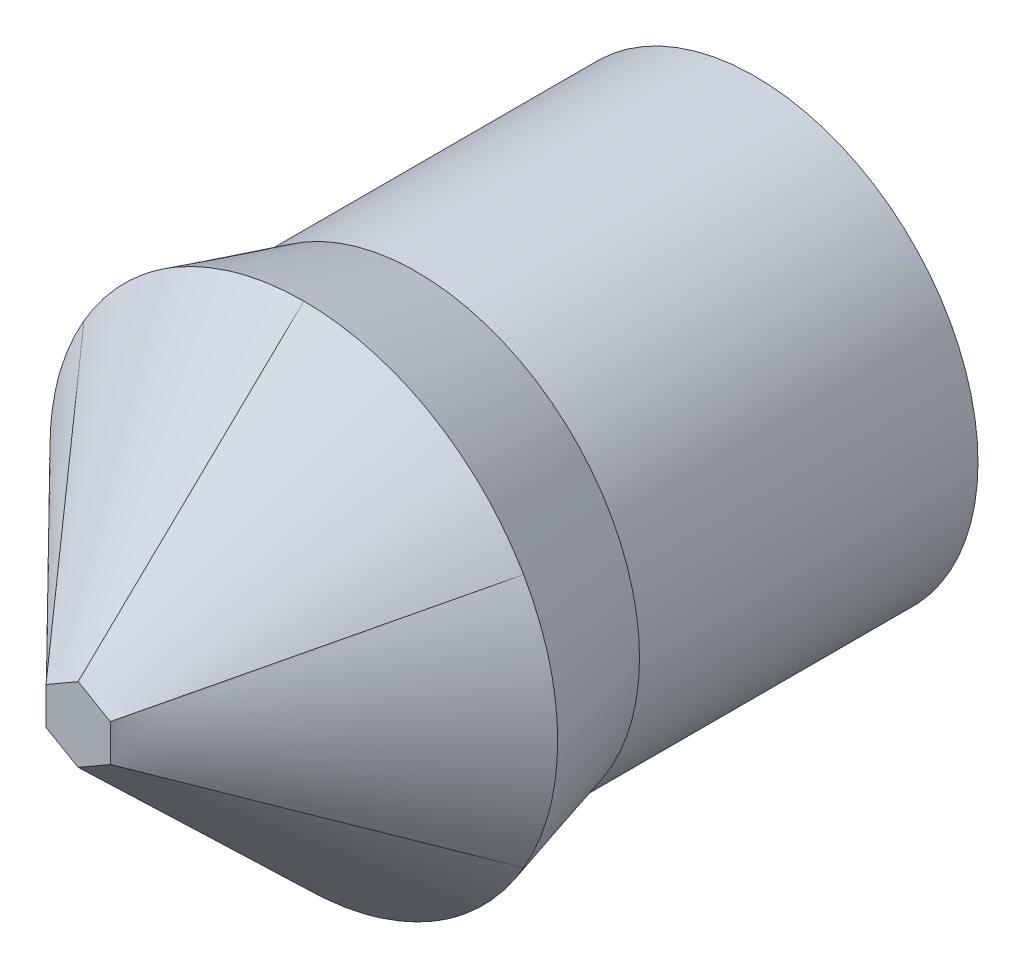
SolidWorks part; units mm, degrees
ref_plane "정면" through (0, 0, 0) normal (0, 0, 1) x (1, 0, 0)
ref_plane "윗면" through (0, 0, 0) normal (0, 1, 0) x (1, 0, 0)
ref_plane "우측면" through (0, 0, 0) normal (1, 0, 0) x (0, 0, -1)
sketch "스케치1" plane through (0, 0, 0) normal (0, 0, 1) x (1, 0, 0)
  circle A0 centre (0, 0) radius 3.95
  dimension "D1" = 7.9
extrude "보스-돌출1" add sketch "스케치1" along normal blind 6
sketch "스케치2" plane through (0, 0, 6) normal (0, 0, 1) x (1, 0, 0)
  circle A0 centre (0, 0) radius 3.95
ref_plane "평면1" through (0, 0, 8) normal (0, 0, 1) x (1, 0, 0)
sketch "스케치3" plane through (0, 0, 8) normal (0, 0, 1) x (1, 0, 0)
  circle A0 centre (0, 0) radius 4.5
  dimension "D1" = 9
loft "로프트1" add profiles "스케치3", "스케치2"
sketch "스케치4" plane through (0, 0, 8) normal (0, 0, 1) x (1, 0, 0)
  circle A0 centre (0, 0) radius 4.5
ref_plane "평면2" through (0, 0, 12) normal (0, 0, 1) x (1, 0, 0)
sketch "스케치5" plane through (0, 0, 12) normal (0, 0, 1) x (1, 0, 0)
  line L1 (0, -0.658) -> (0.5699, -0.329)
  line L2 (0.5699, -0.329) -> (0.5699, 0.329)
  line L3 (0.5699, 0.329) -> (0, 0.658)
  line L4 (0, 0.658) -> (-0.5699, 0.329)
  line L5 (-0.5699, 0.329) -> (-0.5699, -0.329)
  line L6 (-0.5699, -0.329) -> (0, -0.658)
  circle A0 centre (0, 0) radius 0.5699 construction
loft "로프트2" add profiles "스케치5", "스케치4"
